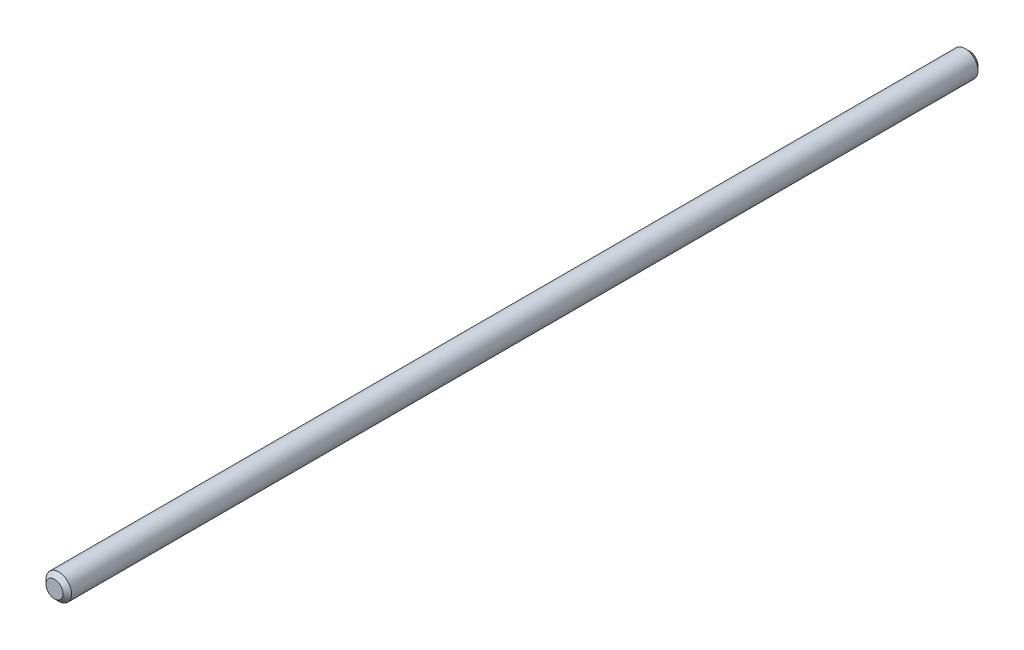
SolidWorks part; units mm, degrees
ref_plane "Front Plane" through (0, 0, 0) normal (0, 0, 1) x (1, 0, 0)
ref_plane "Top Plane" through (0, 0, 0) normal (0, 1, 0) x (1, 0, 0)
ref_plane "Right Plane" through (0, 0, 0) normal (1, 0, 0) x (0, 0, -1)
sketch "Sketch1" plane through (0, 0, 0) normal (0, 0, 1) x (1, 0, 0)
  circle A0 centre (0, 0) radius 3
  dimension "D1" = 6
extrude "Boss-Extrude1" add sketch "Sketch1" along normal mid plane 215
chamfer "Chamfer1" distance 1 angle 45 2 edges at (3, 0, -107.5) (3, 0, 107.5)
